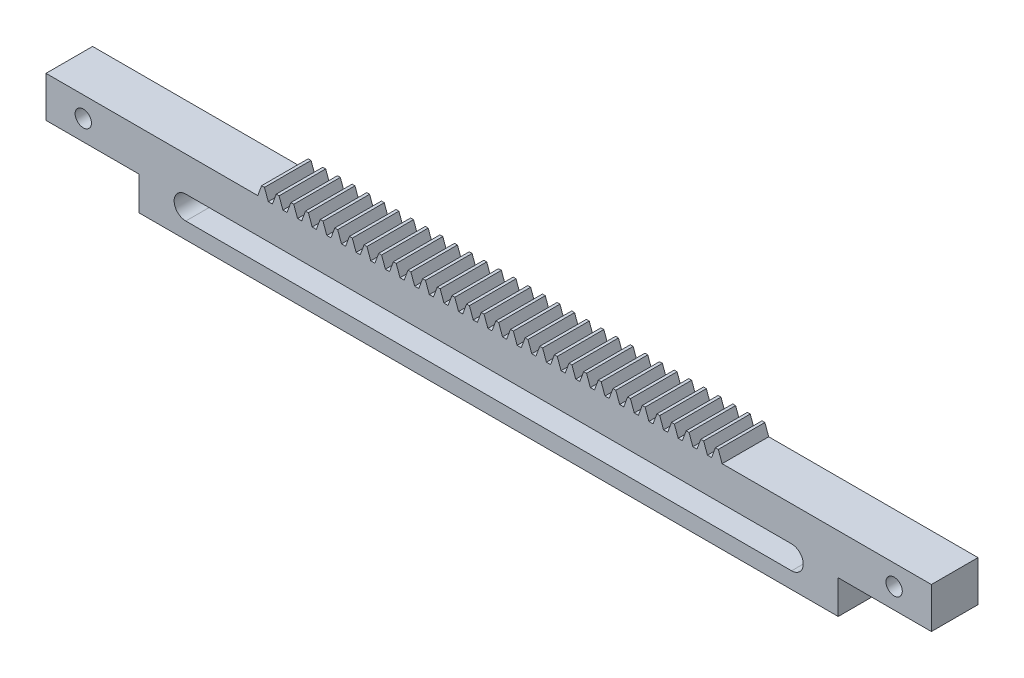
SolidWorks part; units mm, degrees
extrude "Blank" add sketch "BlankSke" against normal blind 10
sketch "BlankSke" plane through (0, 0, 0) normal (0, 0, 1) x (1, 0, 0)
  line L1 (0, 0) -> (100, 0)
  line L2 (0, 0) -> (0, 11)
  line L3 (0, 11) -> (100, 11)
  line L4 (100, 0) -> (100, 11)
  dimension "Length" = 100
  dimension "Blank_height" = 11
ref_plane "Plane1" through (0, 0, 0) normal (0, 0, 1) x (1, 0, 0)
ref_plane "Plane2" through (0, 0, 0) normal (0, 1, 0) x (1, 0, 0)
ref_plane "Plane3" through (0, 0, 0) normal (1, 0, 0) x (0, 0, -1)
sketch "HoldingSke" plane through (0, 0, 0) normal (0, 1, 0) x (1, 0, 0)
  line L0 (0, 0) -> (0.1392, 0.9903)
  line L1 (-15, 0) -> (100, 0) construction
  line L2 (0, 0) -> (-2.1039, 2.3779)
  line L3 (0, 0) -> (-11.863, 4.5341)
  line L4 (0, 0) -> (7.2428, 4.7035)
  line L5 (0, 0) -> (-23.7986, -8.8762)
  line L6 (0, 0) -> (-10.5278, -7.1032)
  line L9 (-71.009, 38.7566) -> (22.9603, 72.9586)
  line L10 (-76.2, 3.3779) -> (-66.2, 3.3779)
  line L11 (0, 0) -> (-10, 0)
  line L12 (-76.2, 101.6) -> (-76.162, 101.6)
  line L13 (24.9733, 27.94) -> (52.9518, 28.4284)
  line L14 (24.9733, 27.94) -> (24.9743, 27.94)
  line L15 (24.9733, 27.94) -> (100.4006, 29.5858)
  circle A0 centre (0, 0) radius 19.05
  circle A1 centre (0, 0) radius 5
  circle A2 centre (0, 0) radius 12.7
  dimension "MPH" = 10
  dimension "Diameter" = 38.1
  dimension "Num_teeth" = 33
  dimension "Pitch" = 1
  dimension "Show_teeth" = 998
  dimension "Thickness" = 12.7
  dimension "Ap" = 20
  dimension "Pitch_height" = 10
  dimension "Width" = 10
  dimension "Backlash" = 0.038
  dimension "Addendum_fac" = 1
  dimension "Dedendum_fac" = 1.25
  dimension "Clearance_fac" = 0.25
  dimension "Dedendum_add" = 0.001
  dimension "Length" = 100
  dimension "Module" = 1
sketch "TooCutSkeIll" plane through (0, 0, 0) normal (0, 0, 1) x (1, 0, 0)
  line L0 (-1.2538, 10.9737) -> (-0.5045, 8.9152)
  line L1 (-0.2687, 8.75) -> (0.2687, 8.75)
  line L2 (0.5045, 8.9152) -> (1.2538, 10.9737)
  line L3 (100, 11) -> (0, 11) construction
  line L4 (0, 0) -> (0, 64.897) construction
  line L5 (-13.208, 10) -> (12.954, 10) construction
  line L6 (0, 0) -> (100, 0) construction
  line L7 (0.8994, 10) -> (0.8994, 48.7463) construction
  line L8 (-0.8994, 10) -> (-0.8994, 48.7463) construction
  line L9 (1.2914, 11) -> (1.2914, 11.0254)
  line L10 (-1.2914, 11) -> (-1.2914, 11.0254)
  line L11 (-1.2914, 11.0254) -> (1.2914, 11.0254)
  arc A0 (0.2687, 8.75) -> (0.5045, 8.9152) centre (0.2687, 9.001) ccw
  arc A1 (-0.5045, 8.9152) -> (-0.2687, 8.75) centre (-0.2687, 9.001) ccw
  arc A2 (1.2914, 11) -> (1.2538, 10.9737) centre (1.2914, 10.96) ccw
  arc A3 (-1.2538, 10.9737) -> (-1.2914, 11) centre (-1.2914, 10.96) ccw
  dimension "Pitch_height" = 10
  dimension "Addendum_plus" = 1.0254
  dimension "Pressure_angle" = 20
  dimension "Gap_width" = 1.7988
  dimension "Dedendum" = 1.25
extrude "ToothCutIll" [suppressed] cut sketch "TooCutSkeIll" against normal through all
sketch "TooCutSkeSim" plane through (0, 0, 0) normal (0, 0, 1) x (1, 0, 0)
  line L0 (0.4444, 8.75) -> (-0.4444, 8.75)
  line L1 (1.2726, 11.0254) -> (0.4444, 8.75)
  line L2 (0, 17.4625) -> (0, 53.467) construction
  line L3 (1.2726, 11.0254) -> (-1.2726, 11.0254)
  line L6 (-1.2726, 11.0254) -> (-0.4444, 8.75)
  line L9 (-0.8994, 10) -> (0.8994, 10) construction
  line L10 (0, 0) -> (100, 0) construction
  line L11 (0.8994, 10) -> (0.8994, 53.467) construction
  line L12 (-0.8994, 10) -> (-0.8994, 53.467) construction
  dimension "Pitch_height" = 10
  dimension "Addendum_plus" = 1.0254
  dimension "Pressure_angle" = 20
  dimension "Gap_width" = 1.7988
  dimension "Dedendum" = 1.25
extrude "ToothCutSim" cut sketch "TooCutSkeSim" against normal through all
pattern_linear "TeethCuts" count 32 spacing 3.1416 along (1, 0, 0) of "ToothCutIll", "ToothCutSim"
sketch "Sketch1" plane through (100, 0, 0) normal (1, 0, 0) x (0, 0, -1)
  line L1 (0, 8.9877) -> (10, 8.9877)
  line L2 (0, 8.9877) -> (0, 0)
  line L3 (0, 0) -> (10, 0)
  line L4 (10, 8.9877) -> (10, 0)
extrude "Boss-Extrude1" add sketch "Sketch1" along normal blind 45
sketch "Sketch2" plane through (0, 0, 0) normal (-1, 0, 0) x (0, 0, 1)
  line L1 (-10, 8.75) -> (0, 8.75)
  line L2 (-10, 8.75) -> (-10, 0)
  line L3 (-10, 0) -> (0, 0)
  line L4 (0, 8.75) -> (0, 0)
extrude "Boss-Extrude2" add sketch "Sketch2" along normal blind 45
sketch "Sketch3" plane through (0, 0, -10) normal (0, 0, -1) x (-1, 0, 0)
  line L0 (45, 8.75) -> (45, 0) construction
  line L1 (-145, 0) -> (-145, 8.9877) construction
  circle A0 centre (-137, 4.375) radius 1.75
  circle A1 centre (37, 4.375) radius 1.75
  point P6 (45, 4.375)
  dimension "D1" = 3.5
  dimension "D2" = 8
  dimension "D3" = 8
extrude "Cut-Extrude1" cut sketch "Sketch3" against normal through all
sketch "Sketch4" plane through (0, 0, 0) normal (0, -1, 0) x (1, 0, 0)
  line L0 (-45, 0) -> (145, 0) construction
  line L1 (-25, 0) -> (125, 0)
  line L2 (-25, 0) -> (-25, -10)
  line L3 (-25, -10) -> (125, -10)
  line L4 (125, 0) -> (125, -10)
  line L5 (-45, -10) -> (145, -10) construction
  line L6 (-45, -10) -> (-45, 0) construction
  line L7 (145, 0) -> (145, -10) construction
  dimension "D1" = 20
  dimension "D2" = 20
extrude "Boss-Extrude3" add sketch "Sketch4" along normal blind 7.2
sketch "Sketch5" plane through (0, 0, 0) normal (0, 0, 1) x (1, 0, 0)
  line L0 (-15, -1.2) -> (115, -1.2) construction
  line L1 (-15, 1.3) -> (115, 1.3)
  line L2 (-15, -3.7) -> (115, -3.7)
  line L3 (-25, -7.2) -> (-25, 0) construction
  line L4 (125, -7.2) -> (125, 0) construction
  line L5 (125, -7.2) -> (-25, -7.2) construction
  arc A0 (-15, 1.3) -> (-15, -3.7) centre (-15, -1.2) ccw
  arc A1 (115, -3.7) -> (115, 1.3) centre (115, -1.2) ccw
  point P2 (50, -1.2)
  dimension "D4" = 2.5
  dimension "D1" = 10
  dimension "D2" = 10
  dimension "D3" = 6
extrude "Cut-Extrude2" cut sketch "Sketch5" against normal through all
sketch "Sketch6" plane through (0, 0, 0) normal (0, 0, 1) x (1, 0, 0)
  line L0 (100, 8.9877) -> (100.0865, 8.75)
  line L1 (100.0865, 8.75) -> (145, 8.75)
  line L2 (145, 8.9877) -> (145, 0) construction
  line L3 (145, 8.75) -> (145, 8.9877)
  line L4 (145, 8.9877) -> (100, 8.9877)
  line L5 (100, 8.9877) -> (99.2676, 11) construction
extrude "Cut-Extrude3" cut sketch "Sketch6" against normal through all
equation "' \"Module@HoldingSke\" = 6.35"
equation "' \"Num_teeth@HoldingSke\" = 12"
equation "' \"Ap@HoldingSke\" =  20"
equation "' \"Ap@HoldingSke\" = 20"
equation "' \"Width@HoldingSke\" = 0.25 * 25.4"
equation "' \"Show_teeth@HoldingSke\" = 500"
equation "' \"Backlash@HoldingSke\" = 0.009 * 25.4"
equation "' \"Addendum_fac@HoldingSke\" = 1.0"
equation "' \"Dedendum_fac@HoldingSke\" = 1.25"
equation "' \"Dedendum_add@HoldingSke\" = 0.00005 * 25.4"
equation "' \"Clearance_fac@HoldingSke\" = 0.25"
equation "' \"Pitch_height@HoldingSke\" = 1 * 25.4"
equation "' \"Length@HoldingSke\" = 4.71 * 25.4"
equation "\"Pitch@HoldingSke\" = 1 / \"Module@HoldingSke\""
equation "\"MPH@HoldingSke\" = \"Dedendum_fac@HoldingSke\" / \"Pitch@HoldingSke\" + 2 * \"Dedendum_add@HoldingSke\" + 0.002 * 25.4"
equation "\"MPH@HoldingSke\" = ((sgn( \"MPH@HoldingSke\" - \"Pitch_height@HoldingSke\")+1)*( \"MPH@HoldingSke\" - \"Pitch_height@HoldingSke\"))/2 + \"Pitch_height@HoldingSke\""
equation "\"Blank_height@BlankSke\" = \"Pitch_height@HoldingSke\" + \"Addendum_fac@HoldingSke\"  / \"Pitch@HoldingSke\" "
equation "\"Length@BlankSke\" =  \"Length@HoldingSke\""
equation "\"Face_width@Blank\" = \"Width@HoldingSke\""
equation "\"Pressure_angle@TooCutSkeIll\" = \"Ap@HoldingSke\""
equation "\"Addendum_plus@TooCutSkeIll\" =  \"Addendum_fac@HoldingSke\"  / \"Pitch@HoldingSke\" + 0.001 *25.4"
equation "\"Dedendum@TooCutSkeIll\" = \"Dedendum_fac@HoldingSke\"  / \"Pitch@HoldingSke\""
equation "\"Pitch_height@TooCutSkeIll\" =  \"MPH@HoldingSke\""
equation "\"Gap_width@TooCutSkeIll\" = 3.14159265 / 2 / \"Pitch@HoldingSke\" + 6 * \"Backlash@HoldingSke\""
equation "\"Pressure_angle@TooCutSkeSim\" = \"Ap@HoldingSke\""
equation "\"Addendum_plus@TooCutSkeSim\" =  \"Addendum_fac@HoldingSke\"  / \"Pitch@HoldingSke\" + 0.001 * 25.4"
equation "\"Dedendum@TooCutSkeSim\" = \"Dedendum_fac@HoldingSke\"  / \"Pitch@HoldingSke\""
equation "\"Pitch_height@TooCutSkeSim\" =  \"MPH@HoldingSke\""
equation "\"Gap_width@TooCutSkeSim\" = 3.14159265 / 2 / \"Pitch@HoldingSke\" + 6 * \"Backlash@HoldingSke\""
equation "\"Root_fillet@TooCutSkeIll\" = \"Clearance_fac@HoldingSke\" / \"Pitch@HoldingSke\" + \"Dedendum_add@HoldingSke\""
equation "\"Break_rad@TooCutSkeIll\" = 0.02 / \"Pitch@HoldingSke\" * 2"
equation "\"Linear_pitch@TeethCuts\" = 3.14159265 / \"Pitch@HoldingSke\""
equation "\"Num_teeth@HoldingSke\" = int( ( \"Length@HoldingSke\" + 0 ) / (3.14159265 / \"Pitch@HoldingSke\")) + 0.9999  + 1"
equation " \"Num_teeth@TeethCuts\" = int( \"Show_teeth@HoldingSke\" ) + 1"
equation " \"Num_teeth@TeethCuts\" = ((sgn( \"Num_teeth@TeethCuts\" - \"Num_teeth@HoldingSke\" )-1)*( \"Num_teeth@TeethCuts\" - \"Num_teeth@HoldingSke\" ))/-2+ \"Num_teeth@HoldingSke\""
equation " \"Num_teeth@TeethCuts\" = ((sgn( \"Num_teeth@TeethCuts\" - 2.0)+1)*( \"Num_teeth@TeethCuts\" - 2.0))/2 +2.0"
